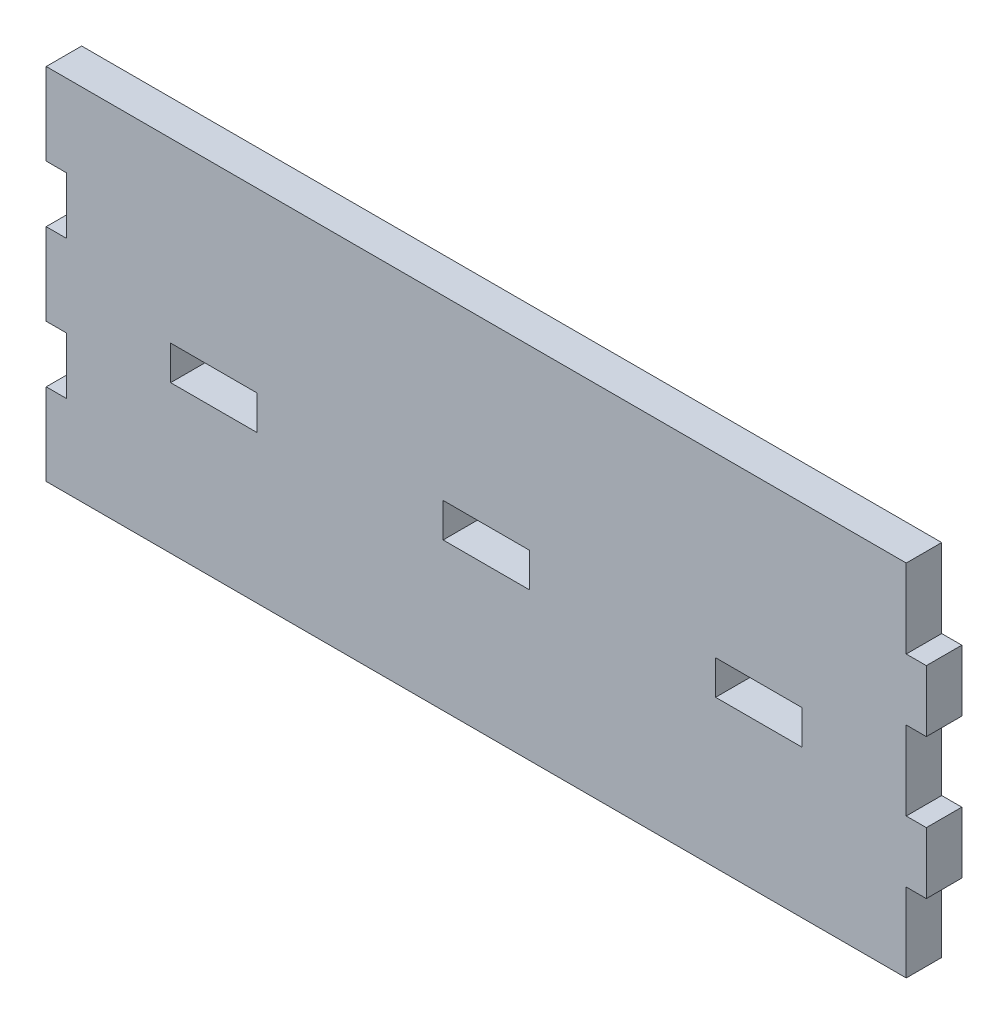
SolidWorks part; units mm, degrees
ref_plane "Спереди" through (0, 0, 0) normal (0, 0, 1) x (1, 0, 0)
ref_plane "Сверху" through (0, 0, 0) normal (0, 1, 0) x (1, 0, 0)
ref_plane "Справа" through (0, 0, 0) normal (1, 0, 0) x (0, 0, -1)
other "Configuration Table"
sketch "Эскиз1" plane through (0, 0, 0) normal (0, 0, 1) x (1, 0, 0)
  line L0 (-71.05, 0.4) -> (71.05, 0.4) construction
  line L1 (-71.05, -30.4) -> (71.05, -30.4)
  line L2 (-71.05, -16.5333) -> (-71.05, -6.9333)
  line L3 (-71.05, 30.4) -> (71.05, 30.4)
  line L4 (71.05, -30.4) -> (71.05, -17.0667)
  line L5 (-71.05, -30.4) -> (71.05, 30.4) construction
  line L6 (-71.05, 30.4) -> (71.05, -30.4) construction
  line L7 (-7.3, 0.4) -> (-7.3, -5.4)
  line L8 (-53.4, 0.4) -> (-38.8, 0.4)
  line L9 (-53.4, 0.4) -> (-53.4, -5.4)
  line L10 (-53.4, -5.4) -> (-38.8, -5.4)
  line L11 (-38.8, 0.4) -> (-38.8, -5.4)
  line L12 (-7.3, 0.4) -> (7.3, 0.4)
  line L13 (7.3, 0.4) -> (7.3, -5.4)
  line L14 (-7.3, -5.4) -> (7.3, -5.4)
  line L15 (38.8, 0.4) -> (38.8, -5.4)
  line L16 (38.8, 0.4) -> (53.4, 0.4)
  line L17 (53.4, 0.4) -> (53.4, -5.4)
  line L18 (38.8, -5.4) -> (53.4, -5.4)
  line L60 (-71.05, 30.4) -> (-74.45, 30.4)
  line L62 (-71.05, 16.5333) -> (-74.45, 16.5333)
  line L63 (-74.45, 30.4) -> (-74.45, 16.5333)
  line L64 (-71.05, 6.9333) -> (-74.45, 6.9333)
  line L65 (-74.45, 6.9333) -> (-74.45, -6.9333)
  line L66 (-71.05, -6.9333) -> (-74.45, -6.9333)
  line L68 (-71.05, -16.5333) -> (-74.45, -16.5333)
  line L69 (-74.45, -16.5333) -> (-74.45, -30.4)
  line L70 (-71.05, -30.4) -> (-74.45, -30.4)
  line L72 (71.05, 17.0667) -> (74.45, 17.0667)
  line L74 (71.05, 6.6667) -> (74.45, 6.6667)
  line L75 (74.45, 17.0667) -> (74.45, 6.6667)
  line L76 (71.05, -6.6667) -> (74.45, -6.6667)
  line L77 (74.45, -6.6667) -> (74.45, -17.0667)
  line L78 (71.05, -17.0667) -> (74.45, -17.0667)
  line L79 (-71.05, 6.9333) -> (-71.05, 16.5333)
  line L80 (71.05, 17.0667) -> (71.05, 30.4)
  line L81 (71.05, -6.6667) -> (71.05, 6.6667)
  line L82 (-71.05, -6.9333) -> (-53.4, -6.9333) construction
  line L83 (71.05, -6.6667) -> (71.05, -17.0667) construction
  line L85 (53.4, 0.4) -> (71.05, 0.4) construction
  point P0 (0, 0)
  point P22 (58.1122, -5.4)
  dimension "D3" = 30
  dimension "D4" = 5.8
  dimension "D6" = 14.6
  dimension "D9" = 3.4
  dimension "D11" = 9.6
  dimension "D12" = 10.4
  dimension "D13" = 3.4
  dimension "D34" = 46.1
  dimension "D35" = 25
  dimension "D2" = 142.1
  dimension "D5" = 17.65
  dimension "D7" = 3
  dimension "D10" = 3
  dimension "D14" = 2
extrude "Бобышка-Вытянуть1" add sketch "Эскиз1" along normal blind 6
equation "\"height\"= 50"
equation "\"width\"=142.1"
equation "\"holes_offset\"= 30"
equation "\"D3@Эскиз1\"=\"holes_offset\""
equation "\"hole_height\"= 5.8"
equation "\"D4@Эскиз1\"=\"hole_height\""
equation "\"hole_offset\"=7.81804"
equation "\"hole_width\"=14.6"
equation "\"D6@Эскиз1\"=\"hole_width\""
equation "\"fanera\"=6"
equation "\"D1@Бобышка-Вытянуть1\"=\"fanera\""
equation "\"out_ship_height\"=3.4"
equation "\"D9@Эскиз1\"=\"out_ship_height\""
equation "\"out_ship_width\"= 9.6"
equation "\"D11@Эскиз1\"=\"out_ship_width\""
equation "\"cnt\"=5"
equation "\"D10@Эскиз1\"=(\"cnt\"+1)/2"
equation "\"in_ship_width\"=10.4"
equation "\"D12@Эскиз1\"=\"in_ship_width\""
equation "\"D13@Эскиз1\"=\"out_ship_height\""
equation "\"D14@Эскиз1\"=(\"cnt\"-1)/2"
equation "\"D2@Эскиз1\"=\"width\""
